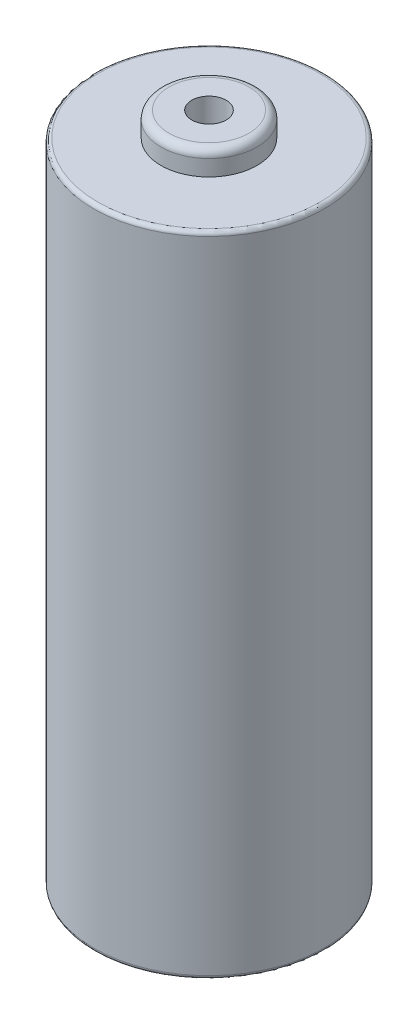
SolidWorks part; units mm, degrees
ref_plane "Front Plane" through (0, 0, 0) normal (0, 0, 1) x (1, 0, 0)
ref_plane "Top Plane" through (0, 0, 0) normal (0, 1, 0) x (1, 0, 0)
ref_plane "Right Plane" through (0, 0, 0) normal (1, 0, 0) x (0, 0, -1)
sketch "Sketch1" plane through (0, 0, 0) normal (0, 1, 0) x (1, 0, 0)
  circle A0 centre (0, 0) radius 3.6576
  dimension "D1" = 7.3152
extrude "Boss-Extrude1" add sketch "Sketch1" along normal mid plane 20.574
fillet "Fillet1" radius 0.127 2 edges at (0, -10.287, 3.6576) (0, 10.287, 3.6576)
sketch "Sketch2" plane through (0, 10.287, 0) normal (0, 1, 0) x (1, 0, 0)
  circle A0 centre (0, 0) radius 1.524
  dimension "D1" = 3.048
extrude "Boss-Extrude2" add sketch "Sketch2" along normal blind 0.762
fillet "Fillet2" radius 0.254 1 edges at (0, 11.049, 1.524)
sketch "Sketch3" plane through (0, 11.049, 0) normal (0, 1, 0) x (1, 0, 0)
  circle A0 centre (0, 0) radius 0.5461
  dimension "D1" = 1.0922
extrude "Cut-Extrude1" cut sketch "Sketch3" against normal blind 10.16
